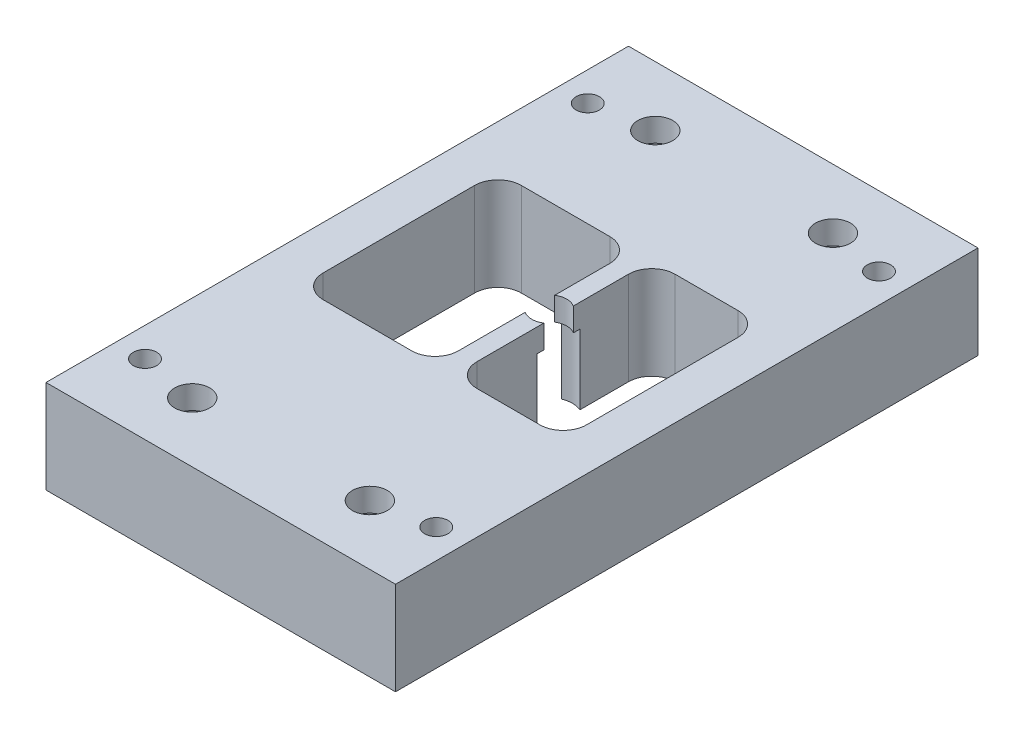
SolidWorks part; units mm, degrees
material "K110"
ref_plane "Front Plane" through (0, 0, 0) normal (0, 0, 1) x (1, 0, 0)
ref_plane "Top Plane" through (0, 0, 0) normal (0, 1, 0) x (1, 0, 0)
ref_plane "Right Plane" through (0, 0, 0) normal (1, 0, 0) x (0, 0, -1)
sketch "Sketch1" plane through (0, 0, 0) normal (0, 1, 0) x (1, 0, 0)
  line L1 (-75, 125) -> (75, 125)
  line L2 (-75, 125) -> (-75, -125)
  line L3 (-75, -125) -> (75, -125)
  line L4 (75, 125) -> (75, -125)
  line L5 (-75, 125) -> (75, -125) construction
  line L6 (-75, -125) -> (75, 125) construction
  point P0 (0, 0)
  dimension "D1" = 250
  dimension "D2" = 150
extrude "Boss-Extrude1" add sketch "Sketch1" against normal blind 40
sketch "Sketch2" plane through (0, 0, 0) normal (0, 1, 0) x (1, 0, 0)
  line L3 (24.75, -27.27) -> (24.75, -11.27) construction
  line L4 (27.75, -8.27) -> (33.88, -8.27) construction
  line L5 (35.88, -6.27) -> (35.88, 11.73) construction
  line L6 (33.88, 13.73) -> (27.75, 13.73) construction
  line L7 (24.75, 42.73) -> (24.75, 16.73) construction
  line L8 (-37.37, 42.73) -> (-13.25, 42.73) construction
  line L9 (-13.25, 42.73) -> (-13.25, 34.23) construction
  line L10 (-14.75, 32.73) -> (-29.37, 32.73) construction
  line L11 (-35.37, 26.73) -> (-35.37, -6.27) construction
  line L12 (-29.37, -12.27) -> (-14.75, -12.27) construction
  line L13 (-13.25, -27.27) -> (-13.25, -13.77) construction
  line L14 (-37.37, -27.27) -> (-13.25, -27.27) construction
  line L15 (-40.37, 39.73) -> (-40.37, -24.27) construction
  line L19 (24.75, -27.27) -> (24.75, -11.27)
  line L20 (27.75, -8.27) -> (33.88, -8.27)
  line L21 (35.88, -6.27) -> (35.88, 11.73)
  line L22 (33.88, 13.73) -> (27.75, 13.73)
  line L23 (24.75, 42.73) -> (24.75, 16.73)
  line L24 (-37.37, 42.73) -> (-13.25, 42.73)
  line L25 (-13.25, 42.73) -> (-13.25, 34.23)
  line L26 (-14.75, 32.73) -> (-29.37, 32.73)
  line L27 (-35.37, 26.73) -> (-35.37, -6.27)
  line L28 (-29.37, -12.27) -> (-14.75, -12.27)
  line L29 (-13.25, -27.27) -> (-13.25, -13.77)
  line L30 (-37.37, -27.27) -> (-13.25, -27.27)
  line L31 (-40.37, 39.73) -> (-40.37, -24.27)
  line L32 (40.88, 42.73) -> (40.88, 39.73) construction
  line L33 (37.88, 42.73) -> (40.88, 42.73) construction
  line L34 (40.88, -27.27) -> (37.88, -27.27) construction
  line L35 (40.88, -24.27) -> (40.88, -27.27) construction
  line L36 (24.75, 42.73) -> (37.88, 42.73) construction
  line L37 (40.88, 39.73) -> (40.88, -24.27) construction
  line L38 (37.88, -27.27) -> (24.75, -27.27) construction
  line L39 (24.75, 42.73) -> (37.88, 42.73)
  line L40 (40.88, 39.73) -> (40.88, -24.27)
  line L41 (37.88, -27.27) -> (24.75, -27.27)
  arc A0 (27.75, -8.27) -> (24.75, -11.27) centre (27.75, -11.27) ccw construction
  arc A1 (33.88, -8.27) -> (35.88, -6.27) centre (33.88, -6.27) ccw construction
  arc A2 (35.88, 11.73) -> (33.88, 13.73) centre (33.88, 11.73) ccw construction
  arc A3 (24.75, 16.73) -> (27.75, 13.73) centre (27.75, 16.73) ccw construction
  arc A4 (-37.37, 42.73) -> (-40.37, 39.73) centre (-37.37, 39.73) ccw construction
  arc A5 (-14.75, 32.73) -> (-13.25, 34.23) centre (-14.75, 34.23) ccw construction
  arc A6 (-29.37, 32.73) -> (-35.37, 26.73) centre (-29.37, 26.73) ccw construction
  arc A7 (-35.37, -6.27) -> (-29.37, -12.27) centre (-29.37, -6.27) ccw construction
  arc A8 (-13.25, -13.77) -> (-14.75, -12.27) centre (-14.75, -13.77) ccw construction
  arc A9 (-40.37, -24.27) -> (-37.37, -27.27) centre (-37.37, -24.27) ccw construction
  arc A10 (27.75, -8.27) -> (24.75, -11.27) centre (27.75, -11.27) ccw
  arc A11 (33.88, -8.27) -> (35.88, -6.27) centre (33.88, -6.27) ccw
  arc A12 (35.88, 11.73) -> (33.88, 13.73) centre (33.88, 11.73) ccw
  arc A13 (24.75, 16.73) -> (27.75, 13.73) centre (27.75, 16.73) ccw
  arc A14 (-37.37, 42.73) -> (-40.37, 39.73) centre (-37.37, 39.73) ccw
  arc A15 (-14.75, 32.73) -> (-13.25, 34.23) centre (-14.75, 34.23) ccw
  arc A16 (-29.37, 32.73) -> (-35.37, 26.73) centre (-29.37, 26.73) ccw
  arc A17 (-35.37, -6.27) -> (-29.37, -12.27) centre (-29.37, -6.27) ccw
  arc A18 (-13.25, -13.77) -> (-14.75, -12.27) centre (-14.75, -13.77) ccw
  arc A19 (-40.37, -24.27) -> (-37.37, -27.27) centre (-37.37, -24.27) ccw
  arc A20 (40.88, 39.73) -> (37.88, 42.73) centre (37.88, 39.73) ccw construction
  arc A21 (37.88, -27.27) -> (40.88, -24.27) centre (37.88, -24.27) ccw construction
  arc A22 (40.88, 39.73) -> (37.88, 42.73) centre (37.88, 39.73) ccw
  arc A23 (37.88, -27.27) -> (40.88, -24.27) centre (37.88, -24.27) ccw
sketch "Sketch3" plane through (0, 0, 0) normal (0, 1, 0) x (1, 0, 0)
  line L1 (-56.25, 50.23) -> (1.75, 50.23)
  line L2 (-56.25, 50.23) -> (-56.25, -34.77)
  line L3 (-56.25, -34.77) -> (1.75, -34.77)
  line L4 (1.75, 50.23) -> (1.75, -34.77)
  line L5 (9.75, 50.23) -> (56.75, 50.23)
  line L6 (9.75, 50.23) -> (9.75, -34.77)
  line L7 (9.75, -34.77) -> (56.75, -34.77)
  line L8 (56.75, 50.23) -> (56.75, -34.77)
  line L15 (24.75, 42.73) -> (24.75, 16.73) construction
  line L16 (-13.25, 42.73) -> (-13.25, 34.23) construction
  dimension "D1" = 85
  dimension "D4" = 15
  dimension "D5" = 15
  dimension "D6" = 47
  dimension "D7" = 58
extrude "Cut-Extrude1" cut sketch "Sketch3" against normal up to next
fillet "Fillet1" radius 10 8 edges at (9.75, -20, -50.23) (56.75, -20, 34.77) (56.75, -20, -50.23) (9.75, -20, 34.77) (-56.25, -20, 34.77) (1.75, -20, 34.77) (1.75, -20, -50.23) (-56.25, -20, -50.23)
extrude "Cut-Extrude4" cut sketch "Sketch7" against normal through all
sketch "Sketch7" plane through (269.63, 0, 0) normal (0, 1, 0) x (1, 0, 0)
  circle A0 centre (-263.88, 10.23) radius 7.5
extrude "Cut-Extrude5" cut sketch "Sketch8" against normal blind 30
sketch "Sketch8" plane through (269.63, -40, 0) normal (0, -1, 0) x (1, 0, 0)
  circle A0 centre (-263.88, -10.23) radius 10
hole_wizard "M10 Tapped Hole1" positions "Sketch11" profile "Sketch10" tap size "M10" standard "ISO"
sketch "Sketch11" plane through (0, -40, 0) normal (0, -1, 0) x (-1, 0, 0)
  line L0 (-75, 125) -> (75, 125) construction
  line L1 (-75, -125) -> (-75, 125) construction
  line L2 (75, 125) -> (75, -125) construction
  line L3 (75, -125) -> (-75, -125) construction
  point P0 (-62.5, 112.5)
  point P2 (62.5, 112.5)
  point P4 (62.5, -112.5)
  point P6 (-62.5, -112.5)
  point P17 (0, 0)
  point P18 (0, 0)
  point P19 (0, 0)
  point P20 (0, 0)
  dimension "D1" = 12.5
  dimension "D2" = 12.5
  dimension "D3" = 12.5
  dimension "D4" = 12.5
sketch "Sketch10" plane through (62.5, -40, -112.5) normal (1, 0, 0) x (0, 0, -1)
  line L0 (0, 0) -> (0, 27.0537)
  line L1 (0, 27.0537) -> (4.25, 24.5)
  line L2 (4.25, 24.5) -> (4.25, 0)
  line L5 (4.25, 0) -> (0, 0)
  line L10 (0, 27.0537) -> (-4.25, 24.5) construction
  line L11 (0, -6.35) -> (0, 107.95) construction
  dimension "Tap Drill Dia." = 8.5
  dimension "Tap Drill Depth" = 24.5
  dimension "Drill Angle" = 118
cosmetic thread "Hole Thread1" parameters "D1"=20, "D2"=10
cosmetic thread "Hole Thread2" parameters "D1"=20, "D2"=10
cosmetic thread "Hole Thread3" parameters "D1"=20, "D2"=10
cosmetic thread "Hole Thread4" parameters "D1"=20, "D2"=10
hole_wizard "Ø10.0mm Dowel Hole1" positions "Sketch14" profile "Sketch13" hole size "Ø10.0" standard "ISO" end condition through all
sketch "Sketch14" plane through (0, -40, 0) normal (0, -1, 0) x (-1, 0, 0)
  line L0 (-75, -125) -> (-75, 125) construction
  line L1 (75, 125) -> (75, -125) construction
  circle A0 centre (-62.5, 112.5) radius 4.25 construction
  circle A2 centre (-62.5, -112.5) radius 4.25 construction
  point P0 (-62.5, 95)
  point P2 (-62.5, -95)
  point P4 (62.5, -95)
  point P6 (62.5, 95)
  point P19 (0, 0)
  point P20 (0, 0)
  point P21 (0, 0)
  dimension "D1" = 12.5
  dimension "D2" = 17.5
  dimension "D3" = 12.5
  dimension "D4" = 17.5
sketch "Sketch13" plane through (62.5, -40, -95) normal (1, 0, 0) x (0, 0, -1)
  line L0 (0, 0) -> (0, 40)
  line L1 (0, 40) -> (5, 40)
  line L2 (5, 40) -> (5, 0)
  line L5 (5, 0) -> (0, 0)
  line L11 (0, -6.35) -> (0, 107.95) construction
  dimension "Thru Hole Dia." = 10
  dimension "Thru Hole Depth" = 40
sketch "Sketch15" plane through (0, 0, 0) normal (0, 1, 0) x (1, 0, 0)
  line L0 (-35.37, -71.53) -> (-40.37, -71.53) construction
  line L1 (-37.87, -71.53) -> (-37.87, -99.3708) construction
  line L2 (40.88, -71.53) -> (35.88, -71.53) construction
  line L3 (38.38, -71.53) -> (38.38, -99.3768) construction
  line L4 (-22, 0) -> (22, 0) construction
  circle A0 centre (38.38, -99.3768) radius 7.5
  circle A1 centre (-37.87, -99.3708) radius 7.5
  circle A2 centre (38.38, 99.3768) radius 7.5
  circle A3 centre (-37.87, 99.3708) radius 7.5
  dimension "D1" = 15
extrude "Cut-Extrude6" cut sketch "Sketch15" against normal up to next
sketch "Sketch16" plane through (0, -40, 0) normal (0, -1, 0) x (1, 0, 0)
  circle A0 centre (-37.87, -99.3708) radius 9
  circle A1 centre (38.38, -99.3768) radius 9
  circle A2 centre (38.38, 99.3768) radius 9
  circle A3 centre (-37.87, 99.3708) radius 9
  dimension "D1" = 18
extrude "Cut-Extrude7" cut sketch "Sketch16" against normal blind 30
